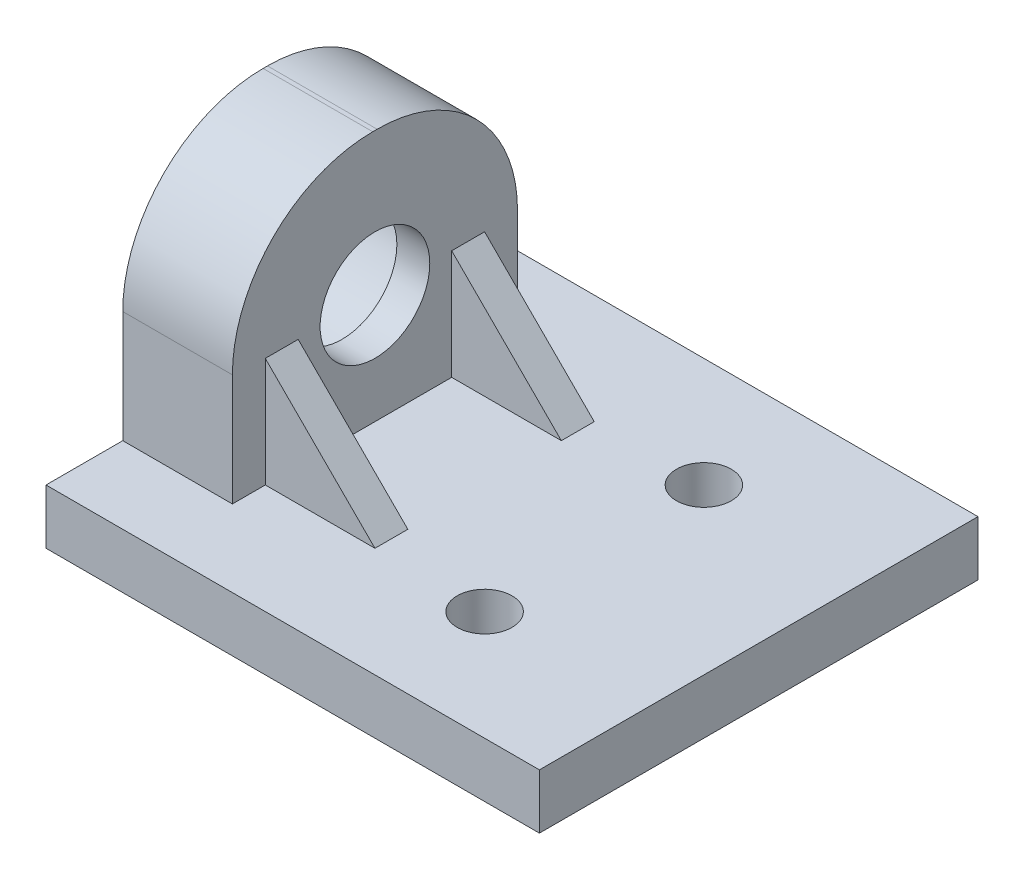
SolidWorks part; units mm, degrees
ref_plane "Front Plane" through (0, 0, 0) normal (0, 0, 1) x (1, 0, 0)
ref_plane "Top Plane" through (0, 0, 0) normal (0, 1, 0) x (1, 0, 0)
ref_plane "Right Plane" through (0, 0, 0) normal (1, 0, 0) x (0, 0, -1)
sketch "Sketch1" plane through (0, 0, 0) normal (0, 1, 0) x (1, 0, 0)
  line L1 (0, 0) -> (57.15, 0)
  line L2 (0, 0) -> (0, 50.8)
  line L3 (0, 50.8) -> (57.15, 50.8)
  line L4 (57.15, 0) -> (57.15, 50.8)
  dimension "D1" = 50.8
  dimension "D2" = 57.15
extrude "Boss-Extrude1" add sketch "Sketch1" along normal blind 25.4
sketch "Sketch2" plane through (0, 0, 0) normal (0, 0, 1) x (1, 0, 0)
  line L0 (57.15, 25.4) -> (57.15, 0) construction
  line L1 (57.15, 19.05) -> (6.35, 19.05)
  line L2 (57.15, 19.05) -> (57.15, 6.35)
  line L3 (57.15, 6.35) -> (6.35, 6.35)
  line L4 (6.35, 19.05) -> (6.35, 6.35)
  line L5 (0, 0) -> (57.15, 0) construction
  line L6 (0, 25.4) -> (57.15, 25.4) construction
  line L7 (0, 25.4) -> (0, 0) construction
  dimension "D1" = 6.35
  dimension "D2" = 6.35
  dimension "D3" = 6.35
extrude "Cut-Extrude1" cut sketch "Sketch2" against normal through all
sketch "Sketch4" plane through (0, 0, 0) normal (-1, 0, 0) x (0, 0, 1)
  line L2 (-50.8, 25.4) -> (0, 25.4) construction
  line L4 (-41.91, 25.4) -> (-8.89, 25.4)
  line L5 (-41.91, 25.4) -> (-41.91, 38.354)
  line L6 (-25.654, 54.61) -> (-25.146, 54.61)
  line L7 (-8.89, 25.4) -> (-8.89, 38.354)
  circle A1 centre (-25.4, 38.1) radius 10.9982
  arc A2 (-41.91, 38.354) -> (-25.654, 54.61) centre (-25.654, 38.354) cw
  arc A3 (-25.146, 54.61) -> (-8.89, 38.354) centre (-25.146, 38.354) cw
  point P7 (-25.4, 25.4)
  dimension "D1" = 16.51
  dimension "D3" = 21.9964
  dimension "D6" = 16.256
  dimension "D2" = 12.7
  dimension "D4" = 16.51
  dimension "D5" = 16.51
extrude "Boss-Extrude2" add sketch "Sketch4" against normal blind 12.7
sketch "Sketch5" plane through (12.7, 0, 0) normal (1, 0, 0) x (0, 0, -1)
  circle A0 centre (25.4, 38.1) radius 6.35
  circle A1 centre (25.4, 38.1) radius 10.9982
  dimension "D1" = 12.7
extrude "Boss-Extrude3" add sketch "Sketch5" against normal blind 3.81
sketch "Sketch8" plane through (0, 0, 0) normal (0, -1, 0) x (1, 0, 0)
  line L0 (0, -25.4) -> (57.15, -25.4) construction
  line L1 (0, -50.8) -> (0, 0) construction
  line L2 (57.15, 0) -> (57.15, -50.8) construction
  line L3 (38.1, 0) -> (38.1, -50.8) construction
  line L4 (0, 0) -> (57.15, 0) construction
  line L5 (57.15, -50.8) -> (0, -50.8) construction
  circle A0 centre (38.1, -38.1) radius 3.175
  circle A1 centre (38.1, -12.7) radius 3.175
  dimension "D2" = 6.35
  dimension "D1" = 19.05
  dimension "D3" = 12.7
extrude "Cut-Extrude2" cut sketch "Sketch8" against normal through all
sketch "Sketch9" plane through (0, 25.4, 0) normal (0, 1, 0) x (1, 0, 0)
  line L0 (12.7, 41.91) -> (12.7, 8.89) construction
  line L1 (12.7, 16.51) -> (25.4, 16.51)
  line L2 (12.7, 16.51) -> (12.7, 12.7)
  line L3 (12.7, 12.7) -> (25.4, 12.7)
  line L4 (25.4, 16.51) -> (25.4, 12.7)
  line L5 (0, 0) -> (57.15, 0) construction
  line L6 (12.7, 25.4) -> (57.15, 25.4) construction
  line L7 (57.15, 0) -> (57.15, 50.8) construction
  line L8 (12.7, 38.1) -> (25.4, 38.1)
  line L9 (25.4, 34.29) -> (25.4, 38.1)
  line L10 (12.7, 34.29) -> (25.4, 34.29)
  line L11 (12.7, 34.29) -> (12.7, 38.1)
  dimension "D1" = 12.7
  dimension "D2" = 12.7
  dimension "D3" = 3.81
extrude "Boss-Extrude5" add sketch "Sketch9" along normal blind 12.7
sketch "Sketch10" plane through (0, 0, -12.7) normal (0, 0, 1) x (1, 0, 0)
  line L0 (25.4, 25.4) -> (25.4, 38.1)
  line L1 (25.4, 38.1) -> (12.7, 38.1)
  line L2 (12.7, 38.1) -> (25.4, 25.4)
extrude "Cut-Extrude3" cut sketch "Sketch10" against normal through all
sketch "Sketch11" plane through (0, 0, 0) normal (0, 0, 1) x (1, 0, 0)
  line L0 (6.35, 19.05) -> (0, 19.05)
  line L1 (0, 19.05) -> (0, 0)
  line L8 (57.15, 0) -> (57.15, 6.35)
  line L9 (57.15, 6.35) -> (6.35, 6.35)
  line L10 (6.35, 6.35) -> (6.35, 19.05)
  line L11 (6.35, 19.05) -> (57.15, 19.05)
  line L12 (57.15, 19.05) -> (57.15, 25.4)
  line L13 (57.15, 25.4) -> (0, 25.4)
  line L14 (0, 25.4) -> (0, 0)
  line L15 (0, 0) -> (57.15, 0)
  line L16 (57.15, 0) -> (57.15, 6.35)
  line L17 (57.15, 6.35) -> (6.35, 6.35)
  line L18 (6.35, 6.35) -> (6.35, 19.05)
  line L22 (0, 19.05) -> (0, 0)
  line L23 (0, 0) -> (57.15, 0)
  line M9 (57.15, 0) -> (57.15, 6.35)
  line M10 (57.15, 6.35) -> (6.35, 6.35)
  line M11 (6.35, 6.35) -> (6.35, 19.05)
  line M15 (0, 25.4) -> (0, 0)
  line M16 (0, 0) -> (57.15, 0)
  dimension "D1" = 0
extrude "Cut-Extrude4" cut sketch "Sketch11" against normal through all contours L0 M11 M15 M16 M9 M10
